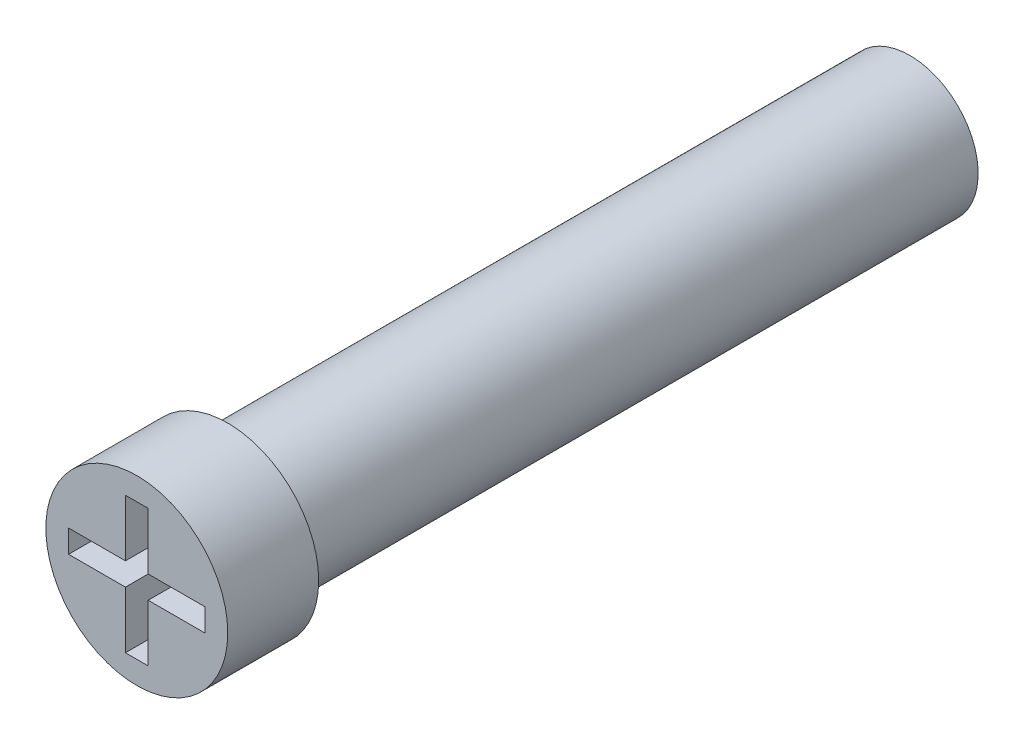
SolidWorks part; units mm, degrees
ref_plane "Front Plane" through (0, 0, 0) normal (0, 0, 1) x (1, 0, 0)
ref_plane "Top Plane" through (0, 0, 0) normal (0, 1, 0) x (1, 0, 0)
ref_plane "Right Plane" through (0, 0, 0) normal (1, 0, 0) x (0, 0, -1)
sketch "Sketch1" plane through (0, 0, 0) normal (0, 0, 1) x (1, 0, 0)
  circle A0 centre (0, 0) radius 2
  dimension "D1" = 4
extrude "Boss-Extrude1" add sketch "Sketch1" along normal blind 2
sketch "Sketch2" plane through (0, 0, 0) normal (0, 0, -1) x (-1, 0, 0)
  circle A0 centre (0, 0) radius 1.5
  dimension "D1" = 3
extrude "Boss-Extrude2" add sketch "Sketch2" along normal blind 15
sketch "Sketch4" plane through (0, 0, 2) normal (0, 0, 1) x (1, 0, 0)
  line L1 (-1.5, 0.25) -> (1.5, 0.25)
  line L2 (-1.5, 0.25) -> (-1.5, -0.25)
  line L3 (-1.5, -0.25) -> (1.5, -0.25)
  line L4 (1.5, 0.25) -> (1.5, -0.25)
  line L5 (-1.5, 0.25) -> (1.5, -0.25) construction
  line L6 (-1.5, -0.25) -> (1.5, 0.25) construction
  line L7 (-0.25, 1.5) -> (0.25, 1.5)
  line L8 (-0.25, 1.5) -> (-0.25, -1.5)
  line L9 (-0.25, -1.5) -> (0.25, -1.5)
  line L10 (0.25, 1.5) -> (0.25, -1.5)
  line L11 (-0.25, 1.5) -> (0.25, -1.5) construction
  line L12 (-0.25, -1.5) -> (0.25, 1.5) construction
  point P0 (0, 0)
  point P6 (0, 0)
  dimension "D1" = 0.5
  dimension "D2" = 0.5
  dimension "D3" = 3
  dimension "D4" = 3
extrude "Cut-Extrude1" cut sketch "Sketch4" against normal blind 1 contours L10 L7 L8 L1 | L10 L1 L8 L3 | L1 L10 L3 L4 | L10 L3 L8 L9 | L8 L1 L2 L3
